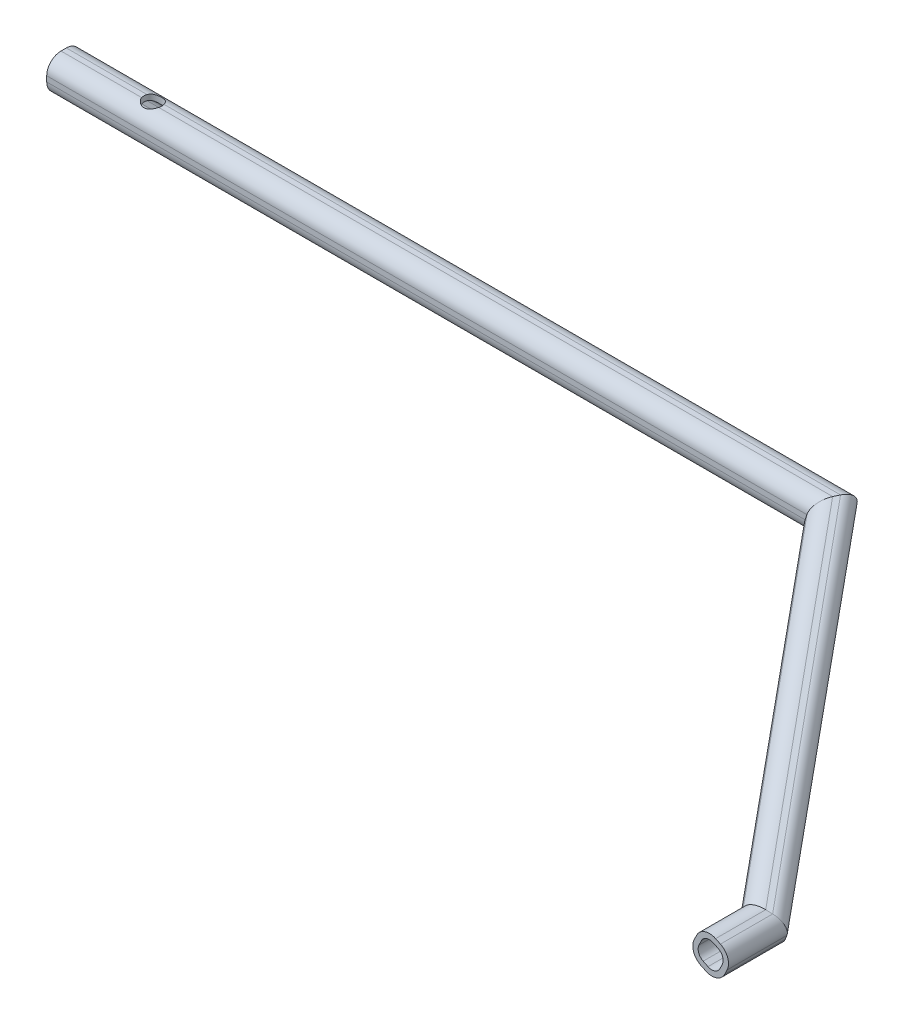
SolidWorks part; units mm, degrees
ref_plane "Front Plane" through (0, 0, 0) normal (0, 0, 1) x (1, 0, 0)
ref_plane "Top Plane" through (0, 0, 0) normal (0, 1, 0) x (1, 0, 0)
ref_plane "Right Plane" through (0, 0, 0) normal (1, 0, 0) x (0, 0, -1)
sketch "Sketch2" plane through (0, 0, 0) normal (1, 0, 0) x (0, 0, -1)
  line L1 (-1.5, -6.5) -> (1.5, -6.5)
  line L2 (-6.5, -1.5) -> (-6.5, 1.5)
  line L3 (-1.5, 6.5) -> (1.5, 6.5)
  line L4 (6.5, -1.5) -> (6.5, 1.5)
  line L5 (-6.5, -6.5) -> (6.5, 6.5) construction
  line L6 (-6.5, 6.5) -> (6.5, -6.5) construction
  arc A0 (6.5, -1.5) -> (1.5, -6.5) centre (1.5, -1.5) cw
  arc A1 (-1.5, -6.5) -> (-6.5, -1.5) centre (-1.5, -1.5) cw
  arc A2 (-6.5, 1.5) -> (-1.5, 6.5) centre (-1.5, 1.5) cw
  arc A3 (1.5, 6.5) -> (6.5, 1.5) centre (1.5, 1.5) cw
  point P0 (0, 0)
  dimension "D3" = 5
  dimension "D1" = 13
  dimension "D2" = 13
sketch3d "3DSketch2"
  line L0 (430, 0, 0) -> (520.0974, 0, 0) construction
  line L1 (430, 0, 0) -> (520.0974, -91.0878, 127.5)
  line L3 (0, 0, 0) -> (430, 0, 0)
  line L4 (520.0974, 0, 0) -> (520.0974, -91.0878, 0) construction
  line L5 (520.0974, -91.0878, 127.5) -> (520.0974, -91.0878, 157.5)
  line L6 (520.0974, -91.0878, 0) -> (520.0974, -91.0878, 127.5) construction
  line L7 (520.0974, -91.0878, 157.5) -> (520.0974, -91.0878, 337.5) construction
  line L8 (520.0974, -91.0878, 337.5) -> (-323.3684, -91.0878, 337.5) construction
  point P11 (0, 0, 0)
  point P12 (524.8245, -90.0499, 164.8905)
  dimension "D1" = 430
  dimension "D2" = 30
  dimension "D3" = 127.5
  dimension "D7" = 180
sweep "Sweep-Thin3" add profiles "Sketch2" path "3DSketch2" parameters "D1"=3
sketch "Sketch21" plane through (0, 0, 0) normal (0, 1, 0) x (1, 0, 0)
  line L0 (0, 0) -> (430, 0) construction
  circle A0 centre (50, 0) radius 5
  dimension "D1" = 10
  dimension "D2" = 50
extrude "Cut-Extrude3" cut sketch "Sketch21" against normal through all both and the other way through all
sketch "Sketch22" [suppressed] plane through (0, 0, 0) normal (0, 0, 1) x (1, 0, 0)
ref_plane "Plane1" [suppressed] through (0, -210, 0) normal (0, 1, 0) x (1, 0, 0)
